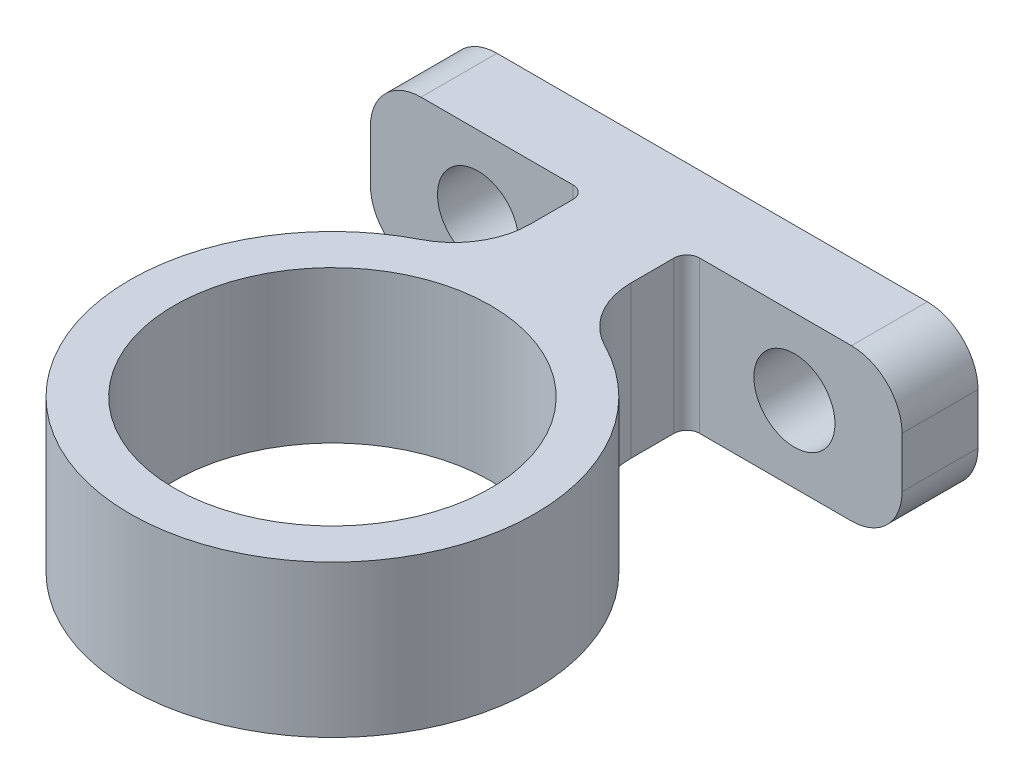
SolidWorks part; units mm, degrees
ref_plane "前视基准面" through (0, 0, 0) normal (0, 0, 1) x (1, 0, 0)
ref_plane "上视基准面" through (0, 0, 0) normal (0, 1, 0) x (1, 0, 0)
ref_plane "右视基准面" through (0, 0, 0) normal (1, 0, 0) x (0, 0, -1)
sketch "草图1" plane through (0, 0, 0) normal (0, 0, 1) x (1, 0, 0)
  line L1 (10.5, -33.2065) -> (-10.5, -33.2065)
  line L2 (10.5, -33.2065) -> (10.5, -27.2065)
  line L3 (10.5, -27.2065) -> (-10.5, -27.2065)
  line L4 (-10.5, -33.2065) -> (-10.5, -27.2065)
  point P5 (-10.5, -35)
  point P6 (0, 0)
  point P7 (0, 0)
  point P9 (10.5001, -35)
  point P12 (0, 0)
  dimension "D1" = 6
  dimension "D2" = 21
extrude "凸台-拉伸1" add sketch "草图1" along normal blind 3
sketch "草图2" plane through (0, -33.2065, 0) normal (0, -1, 0) x (1, 0, 0)
  line L7 (0, 15) -> (0, 0) construction
  line L8 (-10.5, 0) -> (10.5, 0) construction
  line L9 (-2, 7.254) -> (-2, 3)
  line L10 (-10.5, 3) -> (10.5, 3) construction
  line L11 (2, 7.254) -> (2, 3)
  line L12 (-2, 3) -> (2, 3)
  circle A4 centre (0, 15) radius 8
  circle A5 centre (0, 15) radius 6.25
  dimension "D1" = 16
  dimension "D3" = 12.5
  dimension "D2" = 15
  dimension "D4" = 4
extrude "凸台-拉伸2" add sketch "草图2" against normal up to surface (6 mm away)
sketch "草图4" plane through (0, 0, 0) normal (0, 0, -1) x (-1, 0, 0)
  line L0 (-10.5, -30.2065) -> (10.5, -30.2065) construction
  line L1 (-10.5, -33.2065) -> (-10.5, -27.2065) construction
  line L2 (10.5, -27.2065) -> (10.5, -33.2065) construction
  line L3 (0, -27.2065) -> (0, -33.2065) construction
  line L4 (-10.5, -27.2065) -> (10.5, -27.2065) construction
  line L5 (10.5, -33.2065) -> (-10.5, -33.2065) construction
  circle A0 centre (-6.25, -30.2065) radius 1.6
  circle A1 centre (6.25, -30.2065) radius 1.6
  dimension "D1" = 3.2
  dimension "D2" = 12.5
extrude "切除-拉伸1" cut sketch "草图4" against normal up to surface (3 mm away) up to face at (6.25, -30.2065, 3)
fillet "圆角1" radius 0.5 2 edges at (2, -30.2065, 3) (-2, -30.2065, 3)
fillet "圆角2" radius 3 2 edges at (-2, -30.2065, 7.254) (2, -30.2065, 7.254)
fillet "圆角3" radius 2 4 edges at (10.5, -27.2065, 1.5) (-10.5, -27.2065, 1.5) (-10.5, -33.2065, 1.5) (10.5, -33.2065, 1.5)
